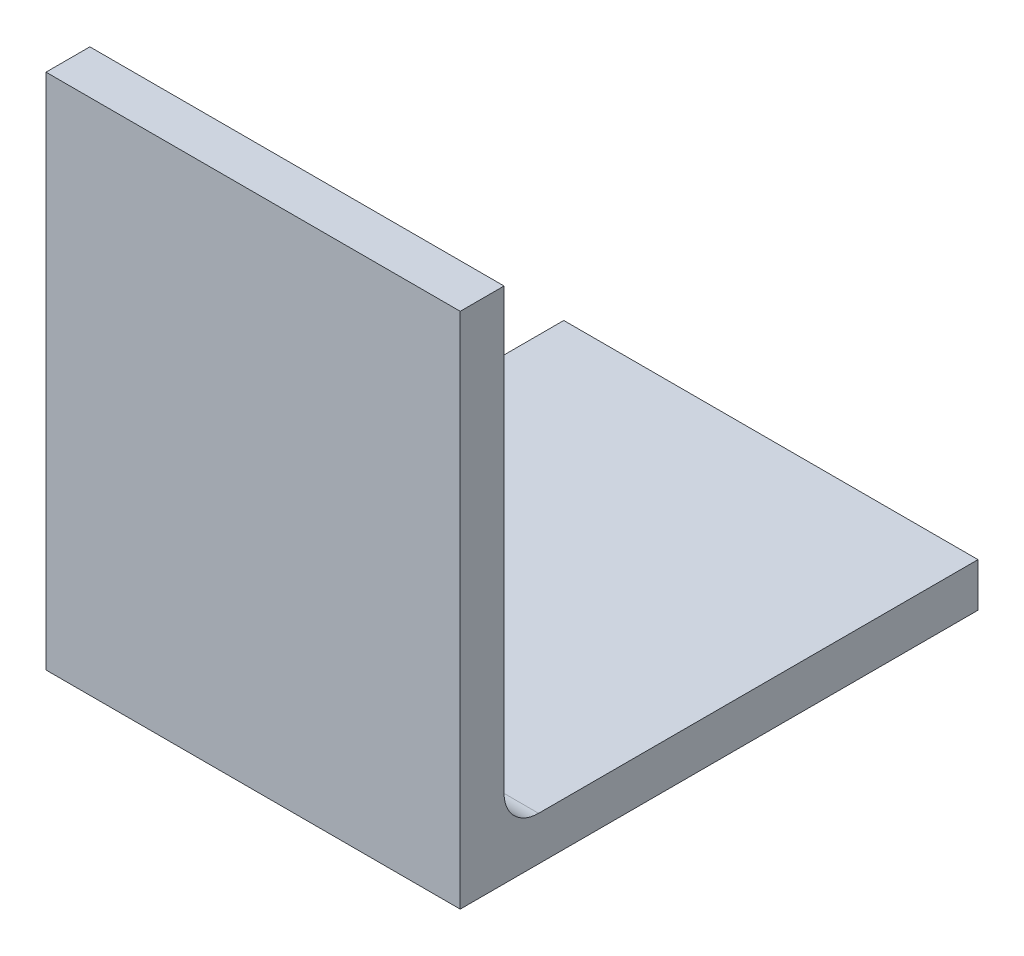
SolidWorks part; units mm, degrees
material "Aleación 1060"
ref_plane "Alzado" through (0, 0, 0) normal (0, 0, 1) x (1, 0, 0)
ref_plane "Planta" through (0, 0, 0) normal (0, 1, 0) x (1, 0, 0)
ref_plane "Vista lateral" through (0, 0, 0) normal (1, 0, 0) x (0, 0, -1)
sketch "Croquis1" plane through (0, 0, 0) normal (1, 0, 0) x (0, 0, -1)
  line L0 (0, 0) -> (0, 150)
  line L1 (0, 0) -> (150, 0)
  line L2 (22.7, 12.7) -> (150, 12.7)
  line L3 (12.7, 22.7) -> (12.7, 150)
  line L4 (150, 0) -> (150, 12.7)
  line L5 (0, 150) -> (12.7, 150)
  line L6 (12.7, 12.7) -> (150, 12.7) construction
  line L7 (12.7, 12.7) -> (12.7, 150) construction
  arc A0 (22.7, 12.7) -> (12.7, 22.7) centre (22.7, 22.7) cw
  dimension "D2" = 10
  dimension "D1" = 12.7
extrude "Saliente-Extruir1" add sketch "Croquis1" along normal mid plane 120
